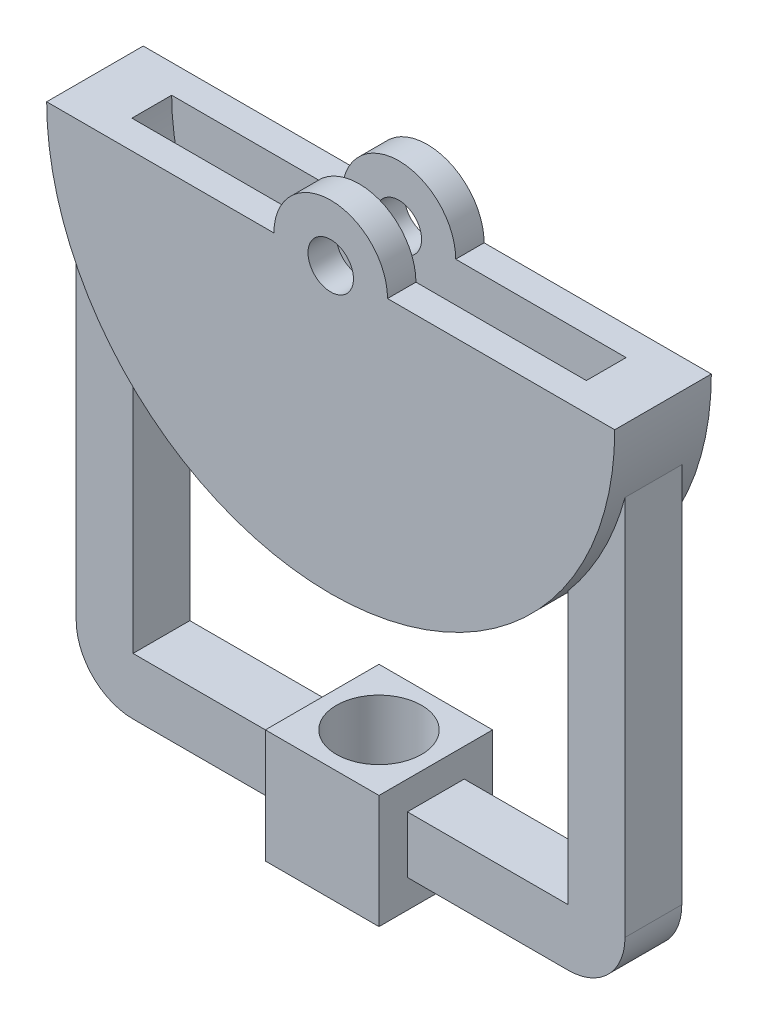
SolidWorks part; units mm, degrees
ref_plane "Front Plane" through (0, 0, 0) normal (0, 0, 1) x (1, 0, 0)
ref_plane "Top Plane" through (0, 0, 0) normal (0, 1, 0) x (1, 0, 0)
ref_plane "Right Plane" through (0, 0, 0) normal (1, 0, 0) x (0, 0, -1)
sketch "Sketch1" plane through (0, 0, 0) normal (0, 0, 1) x (1, 0, 0)
  line L0 (-50, 0) -> (-10, 0)
  line L1 (10, 0) -> (50, 0)
  arc A0 (-50, 0) -> (50, 0) centre (0, 0) ccw
  circle A1 centre (0, 0) radius 4
  arc A2 (10, 0) -> (-10, 0) centre (0, 0) ccw
extrude "Boss-Extrude1" add sketch "Sketch1" along normal blind 5
sketch "Sketch2" plane through (0, 0, 5) normal (0, 0, 1) x (1, 0, 0)
  line L0 (-50, 0) -> (-40, 0)
  line L1 (40, 0) -> (50, 0)
  arc A0 (-50, 0) -> (50, 0) centre (0, 0) ccw
  arc A1 (-40, 0) -> (40, 0) centre (0, 0) ccw
extrude "Boss-Extrude2" add sketch "Sketch2" along normal blind 7
sketch "Sketch3" plane through (0, 0, 12) normal (0, 0, 1) x (1, 0, 0)
  line L0 (-50, 0) -> (-10, 0)
  line L1 (10, 0) -> (50, 0)
  arc A0 (-50, 0) -> (50, 0) centre (0, 0) ccw
  arc A1 (10, 0) -> (-10, 0) centre (0, 0) ccw
  circle A2 centre (0, 0) radius 4
extrude "Boss-Extrude3" add sketch "Sketch3" along normal blind 5
sketch "Sketch4" plane through (0, 0, 17) normal (0, 0, 1) x (1, 0, 0)
  line L1 (0, -75) -> (10, -75)
  line L2 (10, -80) -> (38.2995, -80)
  line L3 (38.2995, -80) -> (38.2995, -32.1426)
  line L4 (-10, -75) -> (10, -75)
  line L5 (-10, -75) -> (-10, -95)
  line L6 (-10, -95) -> (10, -95)
  line L7 (10, -75) -> (10, -95)
  line L8 (10, -90) -> (48.2995, -90)
  line L9 (48.2995, -90) -> (48.2995, -12.9288)
  line L10 (-10, -80) -> (-38.2995, -80)
  line L11 (0, -75) -> (0, -95) construction
  line L12 (-10, -90) -> (-48.2995, -90)
  line L13 (-48.2995, -90) -> (-48.2995, -12.9288)
  line L14 (-38.2995, -80) -> (-38.2995, -32.1426)
  arc A0 (-50, 0) -> (50, 0) centre (0, 0) ccw construction
  arc A2 (-48.2995, -12.9288) -> (-38.2995, -32.1426) centre (0, 0) ccw
  arc A3 (38.2995, -32.1426) -> (48.2995, -12.9288) centre (0, 0) ccw
  arc A4 (-50, 0) -> (50, 0) centre (0, 0) ccw construction
  dimension "D1" = 75
  dimension "D2" = 20
  dimension "D3" = 10
  dimension "D4" = 5
extrude "Boss-Extrude4" add sketch "Sketch4" against normal blind 10 from offset 3.5 offset against normal yes
fillet "Fillet1" radius 10 2 edges at (-48.2995, -90, 8.5) (48.2995, -90, 8.5)
sketch "Sketch7" plane through (0, -95, 0) normal (0, -1, 0) x (1, 0, 0)
  line L0 (-10, 13.5) -> (-38.2995, 13.5) construction
  line L1 (-10, 18.5) -> (10, 18.5)
  line L2 (-10, 18.5) -> (-10, -1.5)
  line L3 (-10, -1.5) -> (10, -1.5)
  line L4 (10, 18.5) -> (10, -1.5)
  dimension "D1" = 20
  dimension "D2" = 5
extrude "Boss-Extrude6" add sketch "Sketch7" against normal blind 20
sketch "Sketch8" plane through (0, -95, 0) normal (0, -1, 0) x (1, 0, 0)
  circle A0 centre (0, 8.5) radius 7.5
extrude "Cut-Extrude2" cut sketch "Sketch8" against normal blind 20 contours A0
